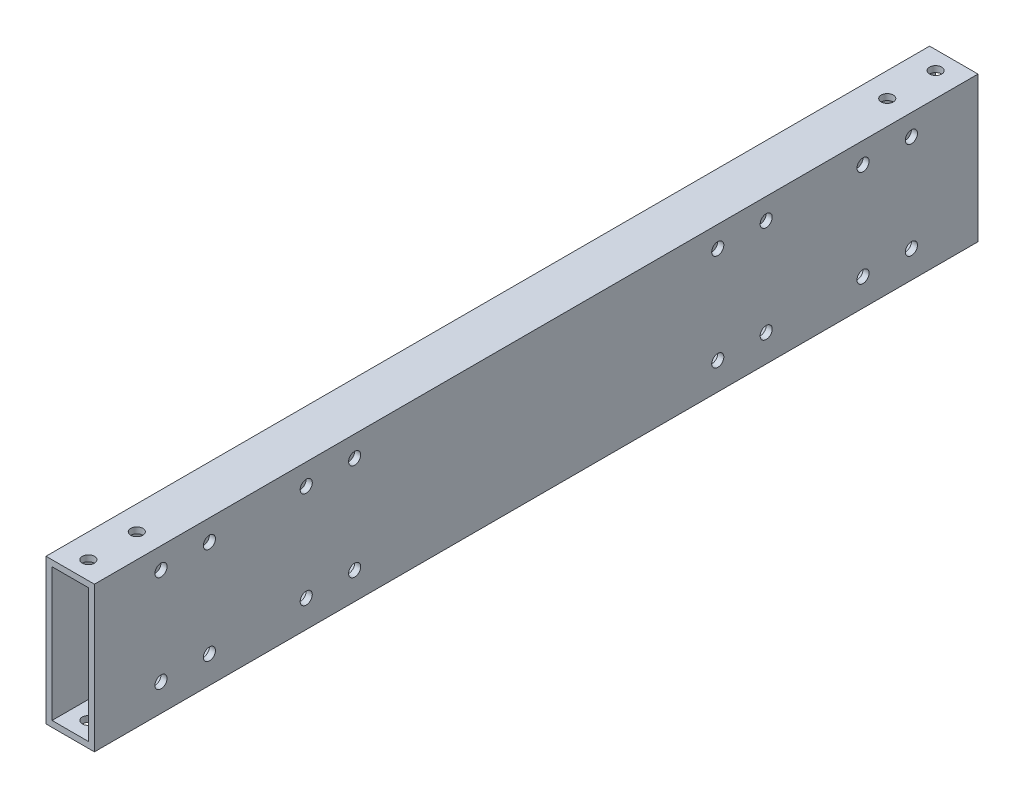
SolidWorks part; units mm, degrees
ref_plane "Front Plane" through (0, 0, 0) normal (0, 0, 1) x (1, 0, 0)
ref_plane "Top Plane" through (0, 0, 0) normal (0, 1, 0) x (1, 0, 0)
ref_plane "Right Plane" through (0, 0, 0) normal (1, 0, 0) x (0, 0, -1)
sketch "Sketch1" plane through (0, 0, 0) normal (0, 0, 1) x (1, 0, 0)
  line L1 (12.7, -38.1) -> (-12.7, -38.1)
  line L2 (12.7, -38.1) -> (12.7, 38.1)
  line L3 (12.7, 38.1) -> (-12.7, 38.1)
  line L4 (-12.7, -38.1) -> (-12.7, 38.1)
  line L5 (12.7, -38.1) -> (-12.7, 38.1) construction
  line L6 (12.7, 38.1) -> (-12.7, -38.1) construction
  line L7 (9.525, -34.925) -> (-9.525, -34.925)
  line L8 (9.525, -34.925) -> (9.525, 34.925)
  line L9 (9.525, 34.925) -> (-9.525, 34.925)
  line L10 (-9.525, -34.925) -> (-9.525, 34.925)
  line L11 (9.525, -34.925) -> (-9.525, 34.925) construction
  line L12 (9.525, 34.925) -> (-9.525, -34.925) construction
  point P0 (0, 0)
  point P6 (0, 0)
  dimension "D1" = 25.4
  dimension "D2" = 76.2
  dimension "D3" = 3.175
  dimension "D4" = 3.175
extrude "Boss-Extrude3" add sketch "Sketch1" along normal blind 463.55
ref_plane "Plane1" through (12.7, 38.1, 0) normal (0, 0, -1) x (-1, 0, 0)
sketch "Sketch6" plane through (0, -38.1, 0) normal (0, -1, 0) x (-1, 0, 0)
  line L0 (-12.7, -463.55) -> (-12.7, 0) construction
  line L1 (12.7, 0) -> (-12.7, 0) construction
  line L2 (12.7, -463.55) -> (12.7, 0) construction
  line L3 (12.7, -463.55) -> (-12.7, -463.55) construction
  circle A0 centre (0, -9.525) radius 3.175
  circle A1 centre (0, -34.925) radius 3.175
  circle A2 centre (0, -454.025) radius 3.175
  circle A3 centre (0, -428.625) radius 3.175
  dimension "D1" = 6.35
  dimension "D2" = 6.35
  dimension "D6" = 12.7
  dimension "D7" = 6.35
  dimension "D8" = 6.35
  dimension "D9" = 12.7
  dimension "D10" = 12.7
  dimension "D12" = 9.525
  dimension "D3" = 12.7
  dimension "D4" = 25.4
  dimension "D5" = 9.525
  dimension "D11" = 25.4
extrude "Cut-Extrude1" cut sketch "Sketch6" against normal blind 806.45
hole_wizard "1/4 (0.25) Diameter Hole1" positions "Sketch7" profile "Sketch9" hole size "1/4" standard "ANSI Inch" end condition through all
sketch "Sketch7" plane through (-12.7, 0, 0) normal (-1, 0, 0) x (0, 0, 1)
  point P0 (136.525, 27.051)
  point P3 (111.125, 27.051)
  point P6 (136.525, -23.749)
  point P9 (111.125, -23.749)
  point P12 (327.025, 27.051)
  point P15 (352.425, 27.051)
  point P18 (327.025, -23.749)
  point P21 (352.425, -23.749)
sketch "Sketch9" plane through (-12.7, 27.051, 136.525) normal (0, 1, 0) x (0, 0, 1)
  line L0 (0, 0) -> (0, 25.4)
  line L1 (0, 25.4) -> (3.175, 25.4)
  line L2 (3.175, 25.4) -> (3.175, 0)
  line L5 (3.175, 0) -> (0, 0)
  line L11 (0, -6.35) -> (0, 107.95) construction
  dimension "Thru Hole Dia." = 6.35
  dimension "Thru Hole Depth" = 25.4
hole_wizard "1/4 (0.25) Diameter Hole2" positions "Sketch12" profile "Sketch13" hole size "1/4" standard "ANSI Inch" end condition through all
sketch "Sketch12" plane through (-12.7, 0, 0) normal (-1, 0, 0) x (0, 0, 1)
  point P0 (34.925, 27.051)
  point P3 (60.325, 27.051)
  point P6 (34.925, -23.749)
  point P9 (60.325, -23.749)
sketch "Sketch13" plane through (-12.7, 27.051, 34.925) normal (0, 1, 0) x (0, 0, 1)
  line L0 (0, 0) -> (0, 25.4)
  line L1 (0, 25.4) -> (3.175, 25.4)
  line L2 (3.175, 25.4) -> (3.175, 0)
  line L5 (3.175, 0) -> (0, 0)
  line L11 (0, -6.35) -> (0, 107.95) construction
  dimension "Thru Hole Dia." = 6.35
  dimension "Thru Hole Depth" = 25.4
hole_wizard "1/4 (0.25) Diameter Hole3" positions "Sketch14" profile "Sketch15" hole size "1/4" standard "ANSI Inch" end condition through all
sketch "Sketch14" plane through (-12.7, 0, 0) normal (-1, 0, 0) x (0, 0, 1)
  point P0 (403.225, 27.051)
  point P3 (428.625, 27.051)
  point P6 (403.225, -23.749)
  point P9 (428.625, -23.749)
sketch "Sketch15" plane through (-12.7, 27.051, 403.225) normal (0, 1, 0) x (0, 0, 1)
  line L0 (0, 0) -> (0, 25.4)
  line L1 (0, 25.4) -> (3.175, 25.4)
  line L2 (3.175, 25.4) -> (3.175, 0)
  line L5 (3.175, 0) -> (0, 0)
  line L11 (0, -6.35) -> (0, 107.95) construction
  dimension "Thru Hole Dia." = 6.35
  dimension "Thru Hole Depth" = 25.4
